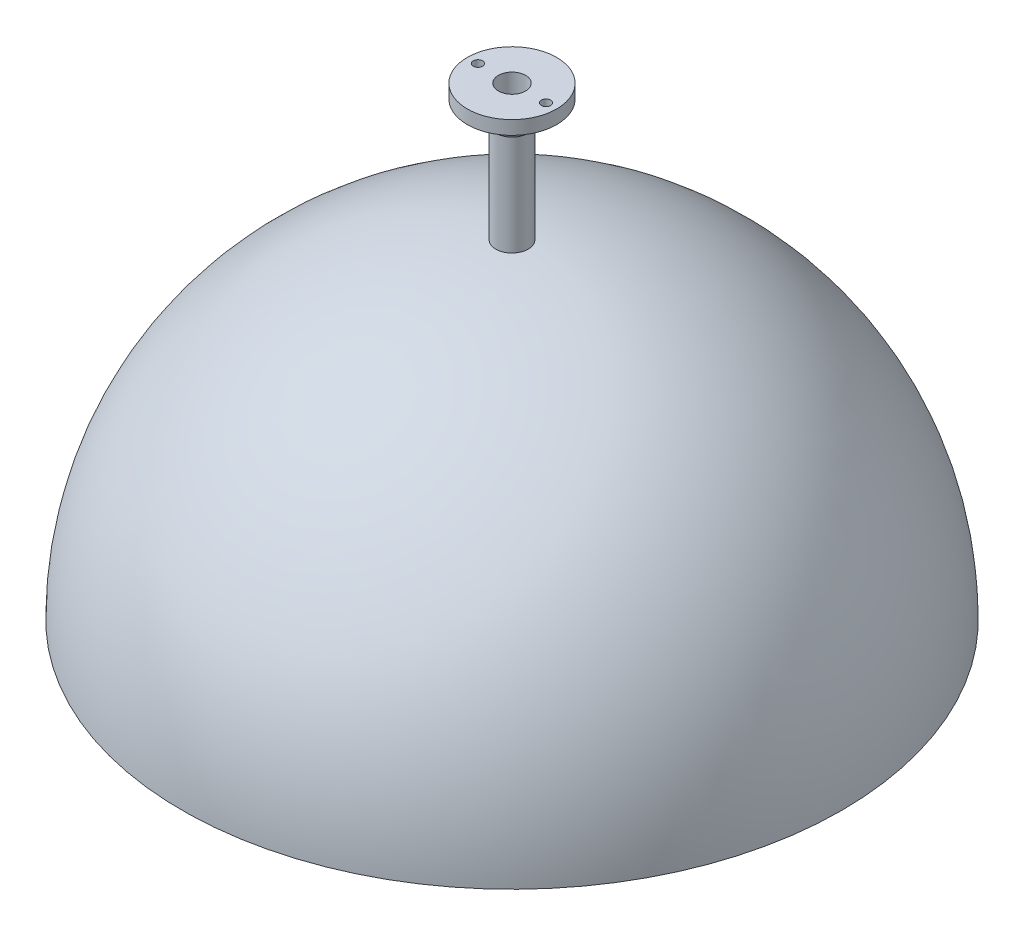
SolidWorks part; units mm, degrees
ref_plane "Front Plane" through (0, 0, 0) normal (0, 0, 1) x (1, 0, 0)
ref_plane "Top Plane" through (0, 0, 0) normal (0, 1, 0) x (1, 0, 0)
ref_plane "Right Plane" through (0, 0, 0) normal (1, 0, 0) x (0, 0, -1)
sketch "Sketch1" plane through (0, 0, 0) normal (0, 0, 1) x (1, 0, 0)
  line L0 (0, 0) -> (0, 775) construction
  line L1 (0, 0) -> (759, 0) construction
  line L2 (0, 759) -> (0, 775)
  line L3 (759, 0) -> (775, 0)
  arc A0 (759, 0) -> (0, 759) centre (0, 0) ccw
  arc A1 (0, 775) -> (775, 0) centre (0, 0) cw
  dimension "D1" = 775
  dimension "D2" = 759
revolve "Revolve1" add sketch "Sketch1" angle 360 about L0
sketch "Sketch2" plane through (0, 0, 0) normal (0, 0, 1) x (1, 0, 0)
  line L0 (0, 775) -> (0, 1093) construction
  line L1 (0, 1093) -> (105, 1093) construction
  line L2 (105, 1093) -> (105, 1061)
  line L3 (0, 1093) -> (38, 1093) construction
  line L4 (38, 1093) -> (38, 774.0678) construction
  line L5 (0, 775) -> (0, 1010) construction
  line L6 (0, 1010) -> (38, 1010) construction
  line L7 (38, 1010) -> (52.624, 1061)
  line L8 (52.624, 1061) -> (105, 1061)
  line L9 (38, 1010) -> (38, 774.0678)
  line L10 (38, 774.0678) -> (32, 774.0678)
  line L11 (32, 774.0678) -> (32, 1093)
  line L12 (32, 1093) -> (105, 1093)
  arc A0 (775, 0) -> (-775, 0) centre (0, 0) ccw construction
  dimension "D1" = 318
  dimension "D2" = 105
  dimension "D3" = 32
  dimension "D4" = 38
  dimension "D5" = 235
  dimension "D6" = 106
  dimension "D7" = 6
revolve "Revolve2" add sketch "Sketch2" angle 360 about L0
sketch "Sketch3" plane through (0, 1093, 0) normal (0, 1, 0) x (1, 0, 0)
  line L0 (-80, 0) -> (80, 0) construction
  circle A0 centre (-80, 0) radius 11
  circle A1 centre (80, 0) radius 11
  point P5 (0, 0)
  dimension "D2" = 22
  dimension "D3" = 22
  dimension "D1" = 160
extrude "Cut-Extrude1" cut sketch "Sketch3" against normal up to next
sketch "Sketch4" plane through (0, 1093, 0) normal (0, 1, 0) x (1, 0, 0)
  circle A0 centre (0, 0) radius 32
extrude "Cut-Extrude2" cut sketch "Sketch4" against normal blind 500
